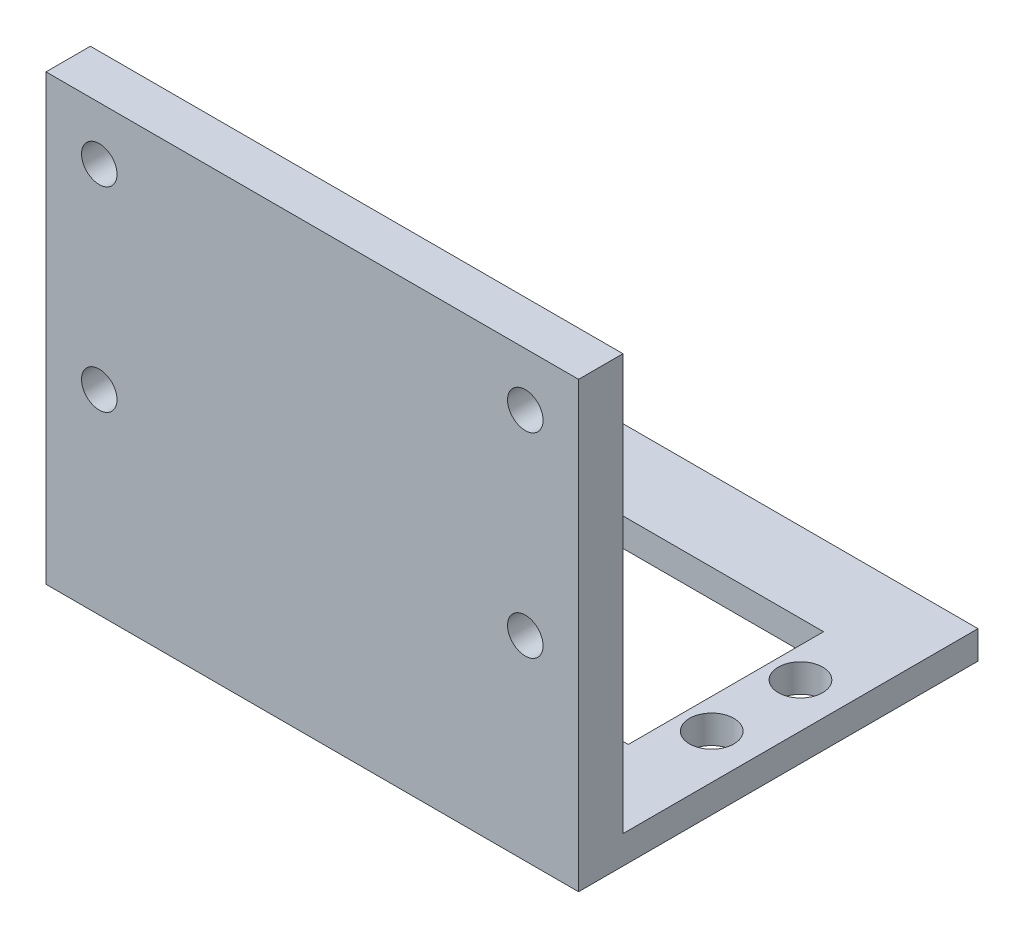
SolidWorks part; units mm, degrees
ref_plane "Front Plane" through (0, 0, 0) normal (0, 0, 1) x (1, 0, 0)
ref_plane "Top Plane" through (0, 0, 0) normal (0, 1, 0) x (1, 0, 0)
ref_plane "Right Plane" through (0, 0, 0) normal (1, 0, 0) x (0, 0, -1)
sketch "Sketch1" plane through (0, 0, 0) normal (0, 1, 0) x (1, 0, 0)
  line L1 (30, -20) -> (-30, -20)
  line L2 (30, -20) -> (30, 20)
  line L3 (30, 20) -> (-30, 20)
  line L4 (-30, -20) -> (-30, 20)
  line L5 (30, -20) -> (-30, 20) construction
  line L6 (30, 20) -> (-30, -20) construction
  line L11 (25, -5) -> (-23.8, -5) construction
  line L12 (25, -5) -> (25, 5) construction
  line L13 (25, 5) -> (-23.8, 5) construction
  line L14 (-23.8, -5) -> (-23.8, 5) construction
  line L15 (25, -5) -> (-23.8, 5) construction
  line L16 (25, 5) -> (-23.8, -5) construction
  line L17 (21.6, -11) -> (-20.4, -11)
  line L18 (21.6, -11) -> (21.6, 11)
  line L19 (21.6, 11) -> (-20.4, 11)
  line L20 (-20.4, -11) -> (-20.4, 11)
  line L21 (21.6, -11) -> (-20.4, 11) construction
  line L22 (21.6, 11) -> (-20.4, -11) construction
  circle A0 centre (25, 5) radius 2.5
  circle A1 centre (-23.8, 5) radius 2.5
  circle A2 centre (-23.8, -5) radius 2.5
  circle A3 centre (25, -5) radius 2.5
  point P0 (0, 0)
  point P6 (0, 0)
  point P7 (0.6, 0)
  point P16 (25, 0)
  point P17 (0.6, 0)
  dimension "D5" = 5
  dimension "D1" = 60
  dimension "D2" = 40
  dimension "D3" = 48.8
  dimension "D4" = 10
  dimension "D6" = 5
  dimension "D7" = 22
  dimension "D8" = 42
extrude "Boss-Extrude1" add sketch "Sketch1" along normal blind 3.175
sketch "Sketch2" plane through (0, 0, 20) normal (0, 0, 1) x (1, 0, 0)
  line L0 (30, 3.175) -> (30, 0) construction
  line L1 (-30, 0) -> (30, 0)
  line L2 (-30, 0) -> (-30, 50)
  line L3 (-30, 50) -> (30, 50)
  line L4 (30, 0) -> (30, 50)
  dimension "D1" = 50
extrude "Boss-Extrude2" add sketch "Sketch2" along normal blind 5
sketch "Sketch3" plane through (0, 0, 20) normal (0, 0, -1) x (-1, 0, 0)
  line L0 (0, 0) -> (0, 50) construction
  line L1 (-30, 0) -> (30, 0) construction
  line L2 (-30, 50) -> (30, 50) construction
  line L3 (-30, 3.175) -> (-30, 50) construction
  point P0 (-24, 44)
  point P1 (24, 44)
  dimension "D1" = 6
  dimension "D2" = 6
hole_wizard "Ø4.0mm Dowel Hole1" positions "Sketch4" profile "Sketch5" hole size "Ø4.0" standard "ANSI Metric" end condition through all
sketch "Sketch4" plane through (0, 0, 20) normal (0, 0, -1) x (-1, 0, 0)
  line L0 (-30, 50) -> (30, 50) construction
  point P0 (-24, 44)
  point P3 (24, 44)
  point P6 (-24, 22)
  point P8 (24, 22)
  point P11 (0, 0)
  point P12 (0, 0)
  point P15 (0, 0)
  point P16 (0, 0)
  dimension "D1" = 28
sketch "Sketch5" plane through (24, 44, 20) normal (1, 0, 0) x (0, 1, 0)
  line L0 (0, 0) -> (0, 5)
  line L1 (0, 5) -> (2, 5)
  line L2 (2, 5) -> (2, 0)
  line L5 (2, 0) -> (0, 0)
  line L11 (0, -6.35) -> (0, 107.95) construction
  dimension "Thru Hole Dia." = 4
  dimension "Thru Hole Depth" = 5
